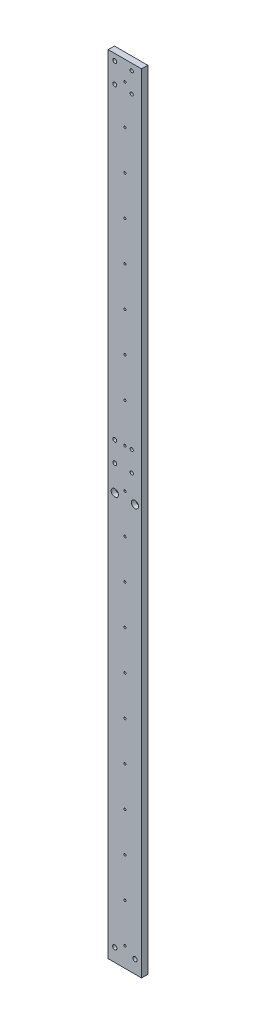
SolidWorks part; units mm, degrees
material "6061-T6 ALUMINUM"
ref_plane "Front/Back" through (0, 0, 0) normal (0, 0, 1) x (1, 0, 0)
ref_plane "Top/Bottom" through (0, 0, 0) normal (0, 1, 0) x (1, 0, 0)
ref_plane "Right/Left" through (0, 0, 0) normal (1, 0, 0) x (0, 0, -1)
sketch "Sketch1" plane through (0, 0, 0) normal (0, 0, 1) x (1, 0, 0)
  line L1 (-25.4, 600) -> (25.4, 600)
  line L2 (-25.4, 600) -> (-25.4, -600)
  line L3 (-25.4, -600) -> (25.4, -600)
  line L4 (25.4, 600) -> (25.4, -600)
  line L5 (0, 0) -> (25.4, 0) construction
  line L6 (0, 0) -> (0, 600) construction
  dimension "D1" = 50.8
  dimension "D2" = 1200
extrude "Extrude1" add sketch "Sketch1" along normal mid plane 9.525
hole_wizard "M4x0.7 Tapped Hole1" positions "Sketch3" profile "Sketch2" tap size "M4x0.7" standard "_*ATS Preferred Ansi METRIC" end condition through all
sketch "Sketch3" plane through (0, 0, 4.7625) normal (0, 0, 1) x (1, 0, 0)
  point P0 (0, 570)
  point P1 (0, 510)
  point P4 (0, 450)
  point P7 (0, 390)
  point P10 (0, 330)
  point P13 (0, 270)
  point P18 (0, 150)
  point P21 (0, 210)
  point P26 (0, 90)
  point P29 (0, 30)
  point P32 (0, -30)
  point P35 (0, -90)
  point P40 (0, -150)
  point P43 (0, -210)
  point P46 (0, -270)
  point P49 (0, -330)
  point P52 (0, -390)
  point P55 (0, -450)
  point P58 (0, -510)
  point P61 (0, -570)
sketch "Sketch2" plane through (0, 570, 4.7625) normal (1, 0, 0) x (0, -1, 0)
  line L0 (0, 0) -> (0, 9.525)
  line L1 (0, 9.525) -> (1.65, 9.525)
  line L2 (1.65, 9.525) -> (1.65, 0)
  line L5 (1.65, 0) -> (0, 0)
  line L11 (0, -6.35) -> (0, 107.95) construction
  dimension "Thru Tap Drill Dia." = 3.3
  dimension "Thru Tap Drill Depth" = 9.525
cosmetic thread "Hole Thread1"
cosmetic thread "Hole Thread2"
cosmetic thread "Hole Thread3"
cosmetic thread "Hole Thread4"
cosmetic thread "Hole Thread5"
cosmetic thread "Hole Thread6"
cosmetic thread "Hole Thread7"
cosmetic thread "Hole Thread8"
cosmetic thread "Hole Thread9"
cosmetic thread "Hole Thread10"
cosmetic thread "Hole Thread11"
cosmetic thread "Hole Thread12"
cosmetic thread "Hole Thread13"
cosmetic thread "Hole Thread14"
cosmetic thread "Hole Thread15"
cosmetic thread "Hole Thread16"
cosmetic thread "Hole Thread17"
cosmetic thread "Hole Thread18"
cosmetic thread "Hole Thread19"
cosmetic thread "Hole Thread20"
hole_wizard "M6 Clearance Hole1" positions "Sketch5" profile "Sketch4" hole size "M6" standard "_*ATS Preferred Ansi METRIC" end condition through all
sketch "Sketch5" plane through (0, 0, 4.7625) normal (0, 0, 1) x (1, 0, 0)
  line L0 (25.4, -600) -> (25.4, 600) construction
  line L1 (-25.4, 600) -> (-25.4, -600) construction
  line L2 (-25.4, -600) -> (25.4, -600) construction
  point P3 (-15.4, -580)
  point P5 (15.4, -580)
  dimension "D1" = 10
  dimension "D2" = 10
  dimension "D3" = 20
sketch "Sketch4" plane through (-15.4, -580, 4.7625) normal (1, 0, 0) x (0, -1, 0)
  line L0 (0, 0) -> (0, 9.525)
  line L1 (0, 9.525) -> (3.3, 9.525)
  line L2 (3.3, 9.525) -> (3.3, 0)
  line L5 (3.3, 0) -> (0, 0)
  line L11 (0, -6.35) -> (0, 107.95) construction
  dimension "Thru Hole Dia." = 6.6
  dimension "Thru Hole Depth" = 9.525
hole_wizard "CBORE for M6 SHCS1" positions "Sketch7" profile "Sketch6" counterbore size "M6" standard "_*ATS Preferred Ansi METRIC" end condition through all
sketch "Sketch7" plane through (0, 0, 4.7625) normal (0, 0, 1) x (1, 0, 0)
  line L0 (25.4, -600) -> (25.4, 600) construction
  line L1 (-25.4, 600) -> (-25.4, -600) construction
  circle A0 centre (15.4, -580) radius 3.3 construction
  point P0 (15.4, 20)
  point P1 (-15.4, 20)
  dimension "D1" = 10
  dimension "D2" = 10
  dimension "D3" = 600
sketch "Sketch6" plane through (15.4, 20, 4.7625) normal (1, 0, 0) x (0, -1, 0)
  line L0 (0, 0) -> (0, 9.525)
  line L1 (0, 9.525) -> (3.3, 9.525)
  line L3 (3.3, 9.525) -> (3.3, 6.8)
  line L4 (3.3, 6.8) -> (5.5, 6.8)
  line L5 (5.5, 6.8) -> (5.5, 0)
  line L7 (5.5, 0) -> (0, 0)
  line L11 (0, -6.35) -> (0, 107.95) construction
  dimension "Thru Hole Dia." = 6.6
  dimension "Thru Hole Depth" = 9.525
  dimension "C'Bore Dia." = 11
  dimension "C'Bore Depth" = 6.8
hole_wizard "Ø6.0 (6) Diameter Hole2" positions "Sketch9" profile "Sketch8" hole size "Ø6.0" standard "Ansi Metric" end condition through all
sketch "Sketch9" plane through (0, 0, -4.7625) normal (0, 0, -1) x (-1, 0, 0)
  point P0 (15.4, 590)
  point P1 (15.4, 559.2)
  point P4 (15.4, 90)
  point P7 (15.4, 59.2)
sketch "Sketch8" plane through (-15.4, 590, -4.7625) normal (1, 0, 0) x (0, 1, 0)
  line L0 (0, 0) -> (0, 9.525)
  line L1 (0, 9.525) -> (3, 9.525)
  line L2 (3, 9.525) -> (3, 0)
  line L5 (3, 0) -> (0, 0)
  line L11 (0, -6.35) -> (0, 107.95) construction
  dimension "Thru Hole Dia." = 6
  dimension "Thru Hole Depth" = 9.525
hole_wizard "M6x1.0 Tapped Hole1" positions "Sketch11" profile "Sketch10" tap size "M6x1.0" standard "_*ATS Preferred Ansi METRIC" end condition through all
sketch "Sketch11" plane through (0, 0, -4.7625) normal (0, 0, -1) x (-1, 0, 0)
  point P0 (-10.4, 559.2)
  point P1 (-10.4, 590)
  point P4 (-10.4, 90)
  point P7 (-10.4, 59.2)
sketch "Sketch10" plane through (10.4, 559.2, -4.7625) normal (1, 0, 0) x (0, 1, 0)
  line L0 (0, 0) -> (0, 9.525)
  line L1 (0, 9.525) -> (2.5, 9.525)
  line L2 (2.5, 9.525) -> (2.5, 0)
  line L5 (2.5, 0) -> (0, 0)
  line L11 (0, -6.35) -> (0, 107.95) construction
  dimension "Thru Tap Drill Dia." = 5
  dimension "Thru Tap Drill Depth" = 9.525
cosmetic thread "Hole Thread21"
cosmetic thread "Hole Thread22"
cosmetic thread "Hole Thread23"
cosmetic thread "Hole Thread24"
